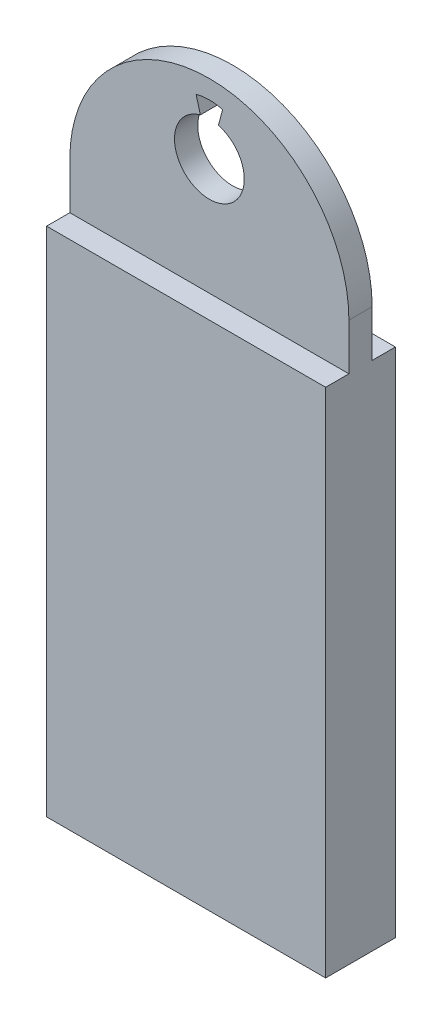
SolidWorks part; units mm, degrees
ref_plane "前视基准面" through (0, 0, 0) normal (0, 0, 1) x (1, 0, 0)
ref_plane "上视基准面" through (0, 0, 0) normal (0, 1, 0) x (1, 0, 0)
ref_plane "右视基准面" through (0, 0, 0) normal (1, 0, 0) x (0, 0, -1)
other "Configuration Table"
sketch "草图1" plane through (0, 0, 0) normal (0, 0, 1) x (1, 0, 0)
  line L0 (-127.9617, 0) -> (-127.9617, 240)
  line L1 (-127.9617, 240) -> (-7.9617, 240)
  line L2 (-7.9617, 240) -> (-7.9617, 0)
  line L3 (-7.9617, 0) -> (-127.9617, 0)
  dimension "D1" = 120
  dimension "D2" = 240
extrude "凸台-拉伸1" add sketch "草图1" along normal blind 30
sketch "草图6" plane through (0, 240, 0) normal (0, 1, 0) x (1, 0, 0)
  line L0 (-127.9617, 0) -> (-7.9617, 0)
  line L1 (-7.9617, 0) -> (-127.9617, 0) construction
  line L2 (-7.9617, -30) -> (-7.9617, 0) construction
  line L3 (-7.9617, 0) -> (-7.9617, -10)
  line L4 (-7.9617, -10) -> (-127.9617, -10)
  line L5 (-127.9617, -30) -> (-127.9617, 0) construction
  line L6 (-127.9617, -10) -> (-127.9617, 0)
  line L7 (-127.9617, -30) -> (-127.9617, -20)
  line L8 (-127.9617, -20) -> (-7.9617, -20)
  line L9 (-7.9617, -20) -> (-7.9617, -30)
  line L10 (-7.9617, -30) -> (-127.9617, -30)
extrude "切除-拉伸2" cut sketch "草图6" against normal blind 20
sketch "草图7" plane through (0, 0, 20) normal (0, 0, 1) x (1, 0, 0)
  line L0 (-127.9617, 240) -> (-7.9617, 240)
  line L1 (-7.9617, 240) -> (-127.9617, 240) construction
  circle A0 centre (-67.9617, 240) radius 60
  line M2 (-7.9617, 240) -> (-127.9617, 240)
extrude "凸台-拉伸4" add sketch "草图7" against normal blind 10 contours A0 M2
sketch "草图8" plane through (0, 0, 20) normal (0, 0, 1) x (1, 0, 0)
  line L0 (-127.9617, 240) -> (-7.9617, 240)
  line L1 (-67.9617, 240) -> (-67.9617, 270)
  line L2 (-67.9617, 270) -> (-73.6557, 291.2504)
  line L3 (-67.9617, 270) -> (-62.2677, 291.2504)
  circle A0 centre (-67.9617, 270) radius 15
  circle A1 centre (-67.9617, 270) radius 22
  dimension "D1" = 30
  dimension "D2" = 30
  dimension "D3" = 30
  dimension "D4" = 44
  dimension "D5" = 165
  dimension "D6" = 30
extrude "切除-拉伸3" cut sketch "草图8" against normal through all contours L3 A1 L2 A0 | L3 A0 L2 | L1 A0 L3 | L2 A0 L1
